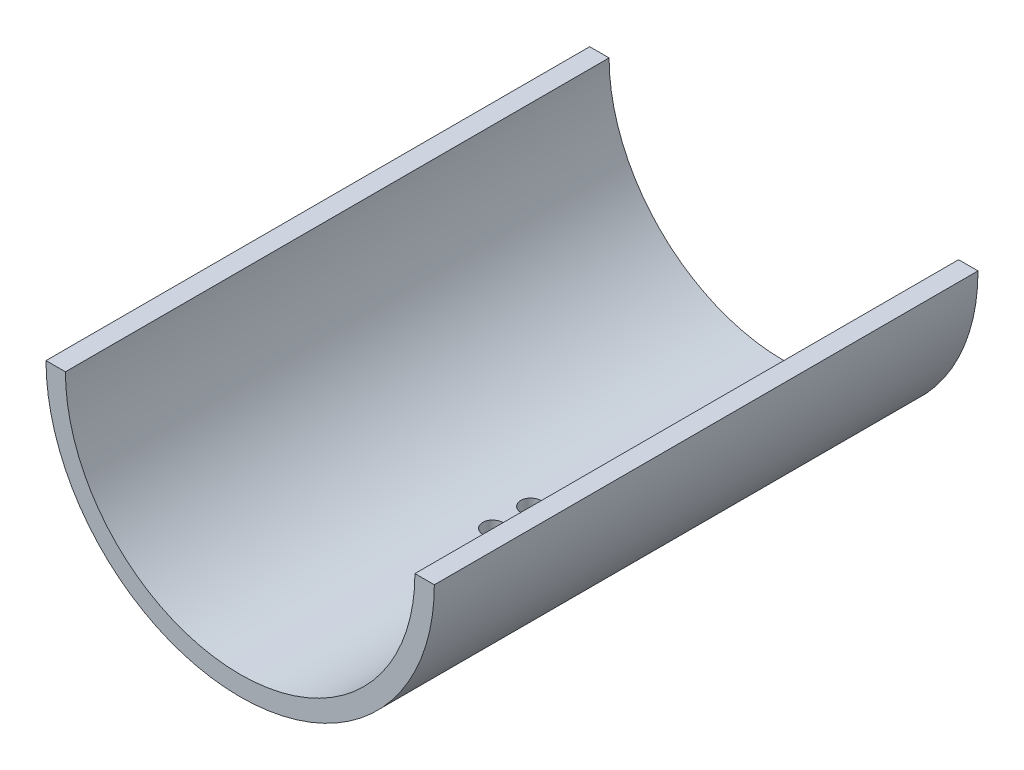
SolidWorks part; units mm, degrees
material "Polyurethane Foam Flexible"
ref_plane "Front Plane" through (0, 0, 0) normal (0, 0, 1) x (1, 0, 0)
ref_plane "Top Plane" through (0, 0, 0) normal (0, 1, 0) x (1, 0, 0)
ref_plane "Right Plane" through (0, 0, 0) normal (1, 0, 0) x (0, 0, -1)
sketch "Sketch2" plane through (0, 0, 0) normal (0, -1, 0) x (0, 0, -1)
  line L0 (0, 0) -> (-66.4006, 0) construction
  line L1 (-28.3687, -63.5) -> (149.4313, -63.5)
  line L2 (-28.3687, -63.5) -> (-28.3687, -57.15)
  line L3 (-28.3687, -57.15) -> (149.4313, -57.15)
  line L4 (149.4313, -63.5) -> (149.4313, -57.15)
  line L5 (-28.3687, -63.5) -> (149.4313, -57.15) construction
  line L6 (-28.3687, -57.15) -> (149.4313, -63.5) construction
  point P0 (60.5313, -60.325)
  dimension "D1" = 6.35
  dimension "D2" = 63.5
  dimension "D3" = 177.8
revolve "Revolve1" add sketch "Sketch2" angle 180 about L0
sketch "Sketch3" plane through (0, 0, 0) normal (0, 1, 0) x (1, 0, 0)
  line L0 (0, 66.7543) -> (0, 54.3083) construction
  line L1 (-57.15, 149.4313) -> (-57.15, -28.3687) construction
  circle A0 centre (0, 66.7543) radius 3.3275
  circle A1 centre (0, 54.3083) radius 3.3275
  point P5 (-57.15, 60.5313)
  point P10 (0, 60.5313)
  dimension "D1" = 6.655
  dimension "D2" = 12.446
extrude "Cut-Extrude1" cut sketch "Sketch3" against normal through all
